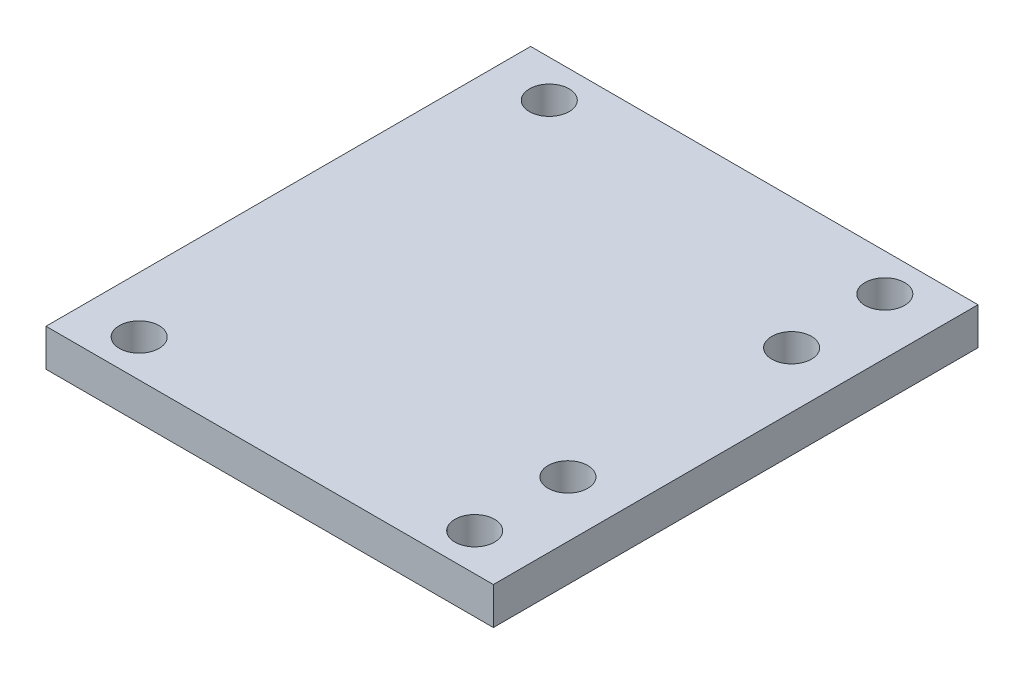
SolidWorks part; units mm, degrees
ref_plane "Front" through (0, 0, 0) normal (0, 0, 1) x (1, 0, 0)
ref_plane "Top" through (0, 0, 0) normal (0, 1, 0) x (1, 0, 0)
ref_plane "Right" through (0, 0, 0) normal (1, 0, 0) x (0, 0, -1)
sketch "Sketch1" plane through (0, 0, 0) normal (0, 1, 0) x (1, 0, 0)
  line L1 (-38.1, -41.275) -> (38.1, -41.275)
  line L2 (-38.1, -41.275) -> (-38.1, 41.275)
  line L3 (-38.1, 41.275) -> (38.1, 41.275)
  line L4 (38.1, -41.275) -> (38.1, 41.275)
  line L5 (-38.1, -41.275) -> (38.1, 41.275) construction
  line L6 (-38.1, 41.275) -> (38.1, -41.275) construction
  point P0 (0, 0)
  dimension "D1" = 76.2
  dimension "D2" = 82.55
extrude "Boss-Extrude1" add sketch "Sketch1" along normal blind 6.35
sketch "Sketch2" plane through (0, 6.35, 0) normal (0, 1, 0) x (1, 0, 0)
  line L0 (-38.1, 34.925) -> (-28.575, 34.925) construction
  line L1 (-38.1, 41.275) -> (-38.1, -41.275) construction
  line L2 (-28.575, 34.925) -> (28.575, 34.925) construction
  line L3 (28.575, 34.925) -> (28.575, 19.05) construction
  line L4 (-38.1, -41.275) -> (38.1, -41.275) construction
  line L5 (28.575, -19.05) -> (28.575, 0) construction
  line L6 (28.575, 0) -> (28.575, 19.05) construction
  line L7 (38.1, 41.275) -> (-38.1, 41.275) construction
  line L8 (38.1, -41.275) -> (38.1, 41.275) construction
  line L9 (-38.1, -34.925) -> (-28.575, -34.925) construction
  line L10 (-28.575, -34.925) -> (28.575, -34.925) construction
  line L11 (28.575, 34.925) -> (38.1, 34.925) construction
  line L12 (28.575, -34.925) -> (28.575, -19.05) construction
  dimension "D1" = 57.15
  dimension "D3" = 38.1
  dimension "D5" = 6.35
  dimension "D7" = 6.35
hole_wizard "1/4 Clearance Hole1" positions "Sketch4" profile "Sketch3" hole size "1/4" standard "ANSI Inch" end condition through all
sketch "Sketch4" plane through (0, 6.35, 0) normal (0, 1, 0) x (-1, 0, 0)
  point P0 (28.575, -34.925)
  point P3 (-28.575, -34.925)
  point P6 (-28.575, -19.05)
  point P12 (-28.575, 19.05)
  point P16 (28.575, 34.925)
  point P19 (-28.575, 34.925)
sketch "Sketch3" plane through (-28.575, 6.35, -34.925) normal (1, 0, 0) x (0, 0, 1)
  line L0 (0, 0) -> (0, 6.35)
  line L1 (0, 6.35) -> (3.3782, 6.35)
  line L2 (3.3782, 6.35) -> (3.3782, 0)
  line L5 (3.3782, 0) -> (0, 0)
  line L11 (0, -6.35) -> (0, 107.95) construction
  dimension "Thru Hole Dia." = 6.7564
  dimension "Thru Hole Depth" = 6.35
